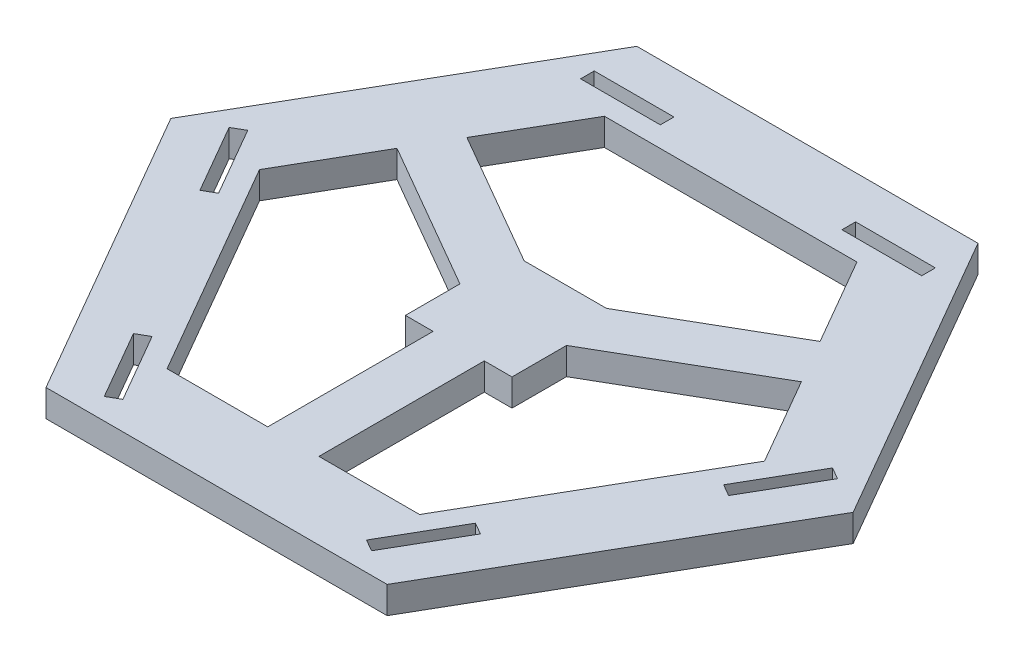
SolidWorks part; units mm, degrees
ref_plane "Front Plane" through (0, 0, 0) normal (0, 0, 1) x (1, 0, 0)
ref_plane "Top Plane" through (0, 0, 0) normal (0, 1, 0) x (1, 0, 0)
ref_plane "Right Plane" through (0, 0, 0) normal (1, 0, 0) x (0, 0, -1)
sketch "Sketch1" plane through (0, 0, 0) normal (0, 1, 0) x (1, 0, 0)
  line L0 (40, -69.282) -> (80, 0)
  line L1 (80, 0) -> (40, 69.282)
  line L2 (-40, 69.282) -> (-80, 0)
  line L3 (-40, -69.282) -> (40, -69.282)
  line L4 (-80, 0) -> (-40, -69.282)
  line L5 (-40, 69.282) -> (40, 69.282)
  line L6 (0, 69.282) -> (0, -69.282) construction
  line L7 (60, -34.641) -> (-60, 34.641) construction
  line L8 (-80, 0) -> (-58.4498, 12.442) construction
  line L9 (-60, -34.641) -> (0, 0) construction
  line L10 (-70.65, -16.1947) -> (-49.0998, -3.7526) construction
  line L11 (-68.5685, 6.6) -> (-59.2185, -9.5947)
  line L12 (-59.2185, -9.5947) -> (-61.9897, -11.1947)
  line L13 (-61.9897, -11.1947) -> (-71.3397, 5)
  line L14 (-71.3397, 5) -> (-68.5685, 6.6)
  line L16 (-31.3397, -64.282) -> (-28.5685, -62.682)
  line L17 (-40.6897, -48.0874) -> (-31.3397, -64.282)
  line L18 (-37.9185, -46.4874) -> (-40.6897, -48.0874)
  line L19 (-28.5685, -62.682) -> (-37.9185, -46.4874)
  line L20 (28.5685, -62.682) -> (37.9185, -46.4874)
  line L21 (37.9185, -46.4874) -> (40.6897, -48.0874)
  line L22 (40.6897, -48.0874) -> (31.3397, -64.282)
  line L23 (31.3397, -64.282) -> (28.5685, -62.682)
  line L24 (71.3397, 5) -> (68.5685, 6.6)
  line L25 (61.9897, -11.1947) -> (71.3397, 5)
  line L26 (59.2185, -9.5947) -> (61.9897, -11.1947)
  line L27 (68.5685, 6.6) -> (59.2185, -9.5947)
  line L28 (40, 56.082) -> (21.3, 56.082)
  line L29 (21.3, 56.082) -> (21.3, 59.282)
  line L30 (21.3, 59.282) -> (40, 59.282)
  line L31 (40, 59.282) -> (40, 56.082)
  line L32 (-40, 59.282) -> (-40, 56.082)
  line L33 (-21.3, 59.282) -> (-40, 59.282)
  line L34 (-21.3, 56.082) -> (-21.3, 59.282)
  line L35 (-40, 56.082) -> (-21.3, 56.082)
  circle A0 centre (0, 0) radius 69.282 construction
  point P13 (-75.325, -8.0973)
  point P35 (75.325, -8.0973)
  dimension "D1" = 80
  dimension "D2" = 80
  dimension "D3" = 9.35
  dimension "D4" = 18.7
  dimension "D5" = 9.35
  dimension "D6" = 3.2
  dimension "D7" = 10
extrude "Boss-Extrude1" add sketch "Sketch1" along normal blind 6.35
sketch "Sketch2" plane through (0, 6.35, 0) normal (0, 1, 0) x (1, 0, 0)
  line L0 (-59.2154, 0) -> (-29.6077, 51.282)
  line L1 (-29.6077, 51.282) -> (29.6077, 51.282)
  line L2 (29.6077, 51.282) -> (59.2154, 0)
  line L3 (59.2154, 0) -> (29.6077, -51.282)
  line L4 (29.6077, -51.282) -> (-29.6077, -51.282)
  line L5 (-29.6077, -51.282) -> (-59.2154, 0)
  line L6 (-80, 0) -> (-40, -69.282) construction
  line L7 (-40, 69.282) -> (-80, 0) construction
  line L8 (40, 69.282) -> (-40, 69.282) construction
  line L9 (80, 0) -> (40, 69.282) construction
  line L10 (40, -69.282) -> (80, 0) construction
  line L11 (-40, -69.282) -> (40, -69.282) construction
  dimension "D1" = 18
  dimension "D2" = 18
  dimension "D3" = 18
  dimension "D4" = 18
  dimension "D5" = 18
  dimension "D6" = 18
extrude "Cut-Extrude1" cut sketch "Sketch2" against normal up to surface (6.35 mm away) up to face at (30.65, 0, -57.682)
sketch "Sketch3" plane through (0, 6.35, 0) normal (0, 1, 0) x (1, 0, 0)
  line L0 (-29.6077, -51.282) -> (29.6077, -51.282) construction
  line L1 (-6, -51.282) -> (6, -51.282)
  line L2 (-6, -51.282) -> (-6, 0)
  line L3 (-6, 0) -> (6, 0)
  line L4 (6, -51.282) -> (6, 0)
  line L5 (44.4115, -25.641) -> (-44.4115, 25.641) construction
  line L6 (29.6077, -51.282) -> (59.2154, 0) construction
  line L7 (-29.6077, 51.282) -> (-59.2154, 0) construction
  line L8 (-44.4115, -25.641) -> (44.4115, 25.641) construction
  line L9 (-59.2154, 0) -> (-29.6077, -51.282) construction
  line L10 (59.2154, 0) -> (29.6077, 51.282) construction
  line L11 (47.4115, 20.4449) -> (3, -5.1962)
  line L12 (-3, 5.1962) -> (3, -5.1962)
  line L13 (41.4115, 30.8372) -> (-3, 5.1962)
  line L14 (41.4115, 30.8372) -> (47.4115, 20.4449)
  line L15 (-41.4115, 30.8372) -> (3, 5.1962)
  line L16 (-3, -5.1962) -> (3, 5.1962)
  line L17 (-47.4115, 20.4449) -> (-3, -5.1962)
  line L18 (-47.4115, 20.4449) -> (-41.4115, 30.8372)
  point P6 (0, 0)
  point P28 (-6, -25.641)
  line M4 (-59.2154, 0) -> (-29.6077, 51.282)
  line M6 (29.6077, 51.282) -> (59.2154, 0)
  line M8 (29.6077, -51.282) -> (-29.6077, -51.282)
  dimension "D1" = 12
extrude "Boss-Extrude2" add sketch "Sketch3" against normal up to surface (6.35 mm away) contours L17 L2 L4 L11 L12 L16 M8 | L16 L3 L4 L11 L13 L15 M6 | L17 L2 L3 L12 L13 L15 M4 | L12 L16 L15 L13 | L3 L12 L11 L4 | L2 L17 L16 L3 up to face at (0, 0, 0)
sketch "Sketch4" plane through (0, 6.35, 0) normal (0, 1, 0) x (1, 0, 0)
  line L1 (-12.5, 12.5) -> (12.5, 12.5)
  line L2 (-12.5, 12.5) -> (-12.5, -12.5)
  line L3 (-12.5, -12.5) -> (12.5, -12.5)
  line L4 (12.5, 12.5) -> (12.5, -12.5)
  line L5 (-12.5, 12.5) -> (12.5, -12.5) construction
  line L6 (-12.5, -12.5) -> (12.5, 12.5) construction
  point P0 (0, 0)
  dimension "D1" = 25
  dimension "D2" = 25
extrude "Boss-Extrude3" add sketch "Sketch4" against normal up to surface (6.35 mm away) up to face at (-29.6469, 0, 17.1167)
equation "\"D5@Sketch1\"=\"D4@Sketch1\"/2"
equation "\"D3@Sketch1\"=\"D5@Sketch1\""
equation "\"D2@Sketch2\"=\"D1@Sketch2\""
equation "\"D3@Sketch2\"=\"D1@Sketch2\""
equation "\"D4@Sketch2\"=\"D1@Sketch2\""
equation "\"D5@Sketch2\"=\"D1@Sketch2\""
equation "\"D6@Sketch2\"=\"D1@Sketch2\""
